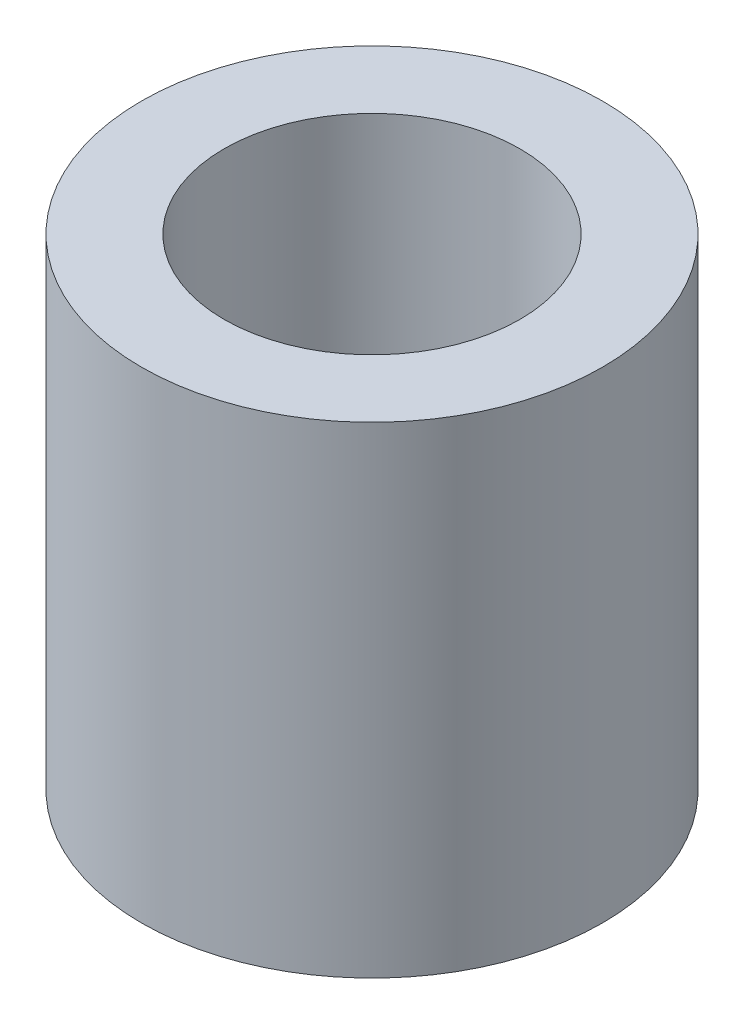
SolidWorks part; units mm, degrees
ref_plane "Front Plane" through (0, 0, 0) normal (0, 0, 1) x (1, 0, 0)
ref_plane "Top Plane" through (0, 0, 0) normal (0, 1, 0) x (1, 0, 0)
ref_plane "Right Plane" through (0, 0, 0) normal (1, 0, 0) x (0, 0, -1)
sketch "Sketch1" plane through (0, 0, 0) normal (0, 1, 0) x (1, 0, 0)
  circle A0 centre (0, 0) radius 2.55
  circle A1 centre (0, 0) radius 3.975
  dimension "D1" = 7.95
  dimension "D2" = 5.1
extrude "Boss-Extrude1" add sketch "Sketch1" along normal mid plane 8.3
